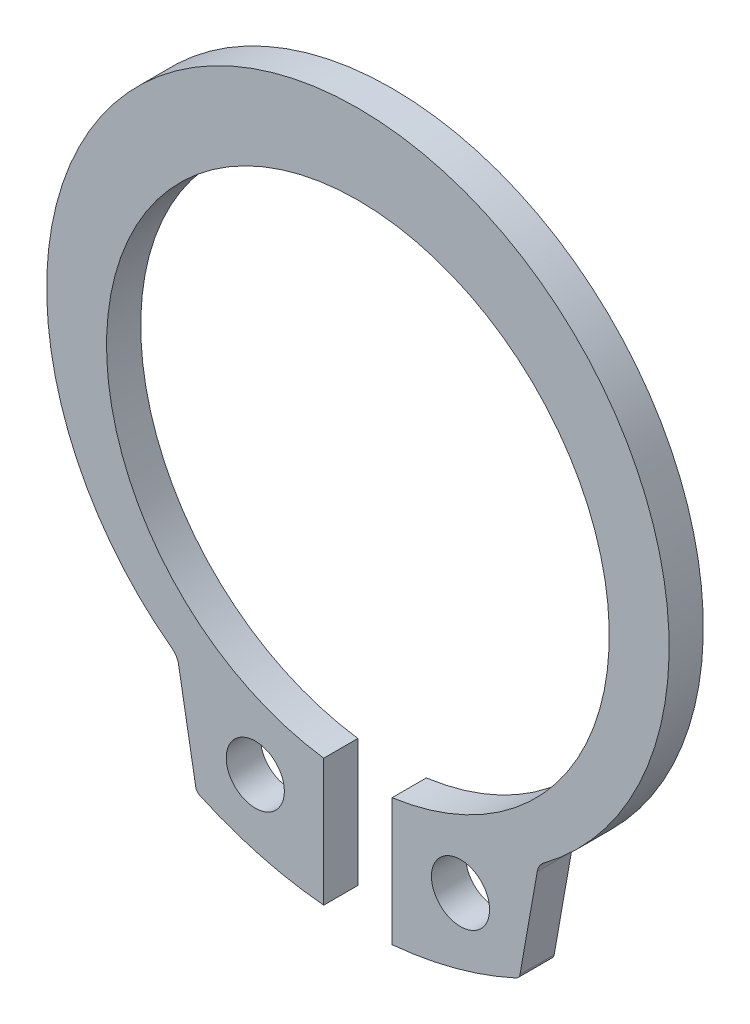
SolidWorks part; units mm, degrees
ref_plane "Front" through (0, 0, 0) normal (0, 0, 1) x (1, 0, 0)
ref_plane "Top" through (0, 0, 0) normal (0, 1, 0) x (1, 0, 0)
ref_plane "Right" through (0, 0, 0) normal (1, 0, 0) x (0, 0, -1)
sketch "Sketch1" plane through (0, 0, 0) normal (0, 0, 1) x (1, 0, 0)
  line L0 (0, 4.2365) -> (0, -4.9012) construction
  line L1 (-1, -7.8617) -> (-1, -11.5847)
  line L2 (1, -7.8617) -> (1, -11.5847)
  line L3 (9.2, -0.58) -> (-9.2, -0.58) construction
  line L4 (5.2784, -7.4127) -> (4.7216, -10.5704)
  line L7 (-5.2784, -7.4127) -> (-4.7216, -10.5704)
  line L8 (-5.2784, -7.4127) -> (-5.2784, -15.4835) construction
  arc A0 (1, -7.8617) -> (-1, -7.8617) centre (0, -0.58) ccw
  arc A1 (5.2784, -7.4127) -> (-5.2784, -7.4127) centre (0, 0) ccw
  arc A2 (-9.2, -0.58) -> (9.2, -0.58) centre (0, -0.58) ccw construction
  arc A3 (4.7216, -10.5704) -> (1, -11.5847) centre (0, -0.58) cw
  arc A4 (-4.7216, -10.5704) -> (-1, -11.5847) centre (0, -0.58) ccw
  circle A5 centre (3, -9.2771) radius 0.85
  circle A6 centre (-3, -9.2771) radius 0.85
  point P17 (-5, -8.9916)
  dimension "d" = 14.7
  dimension "D2" = 10
  dimension "d0" = 18.2
  dimension "d1" = 1.7
  dimension "R1" = 9.2
  dimension "R" = 11.05
  dimension "B1" = 2
  dimension "C" = 0.58
  dimension "L" = 10
  dimension "B2" = 6
extrude "Body" add sketch "Sketch1" against normal blind 1
fillet "Fillet1" radius 0.2 2 edges at (-4.7216, -10.5704, -0.5) (4.7216, -10.5704, -0.5)
fillet "Fillet2" radius 0.5 2 edges at (5.2784, -7.4127, -0.5) (-5.2784, -7.4127, -0.5)
